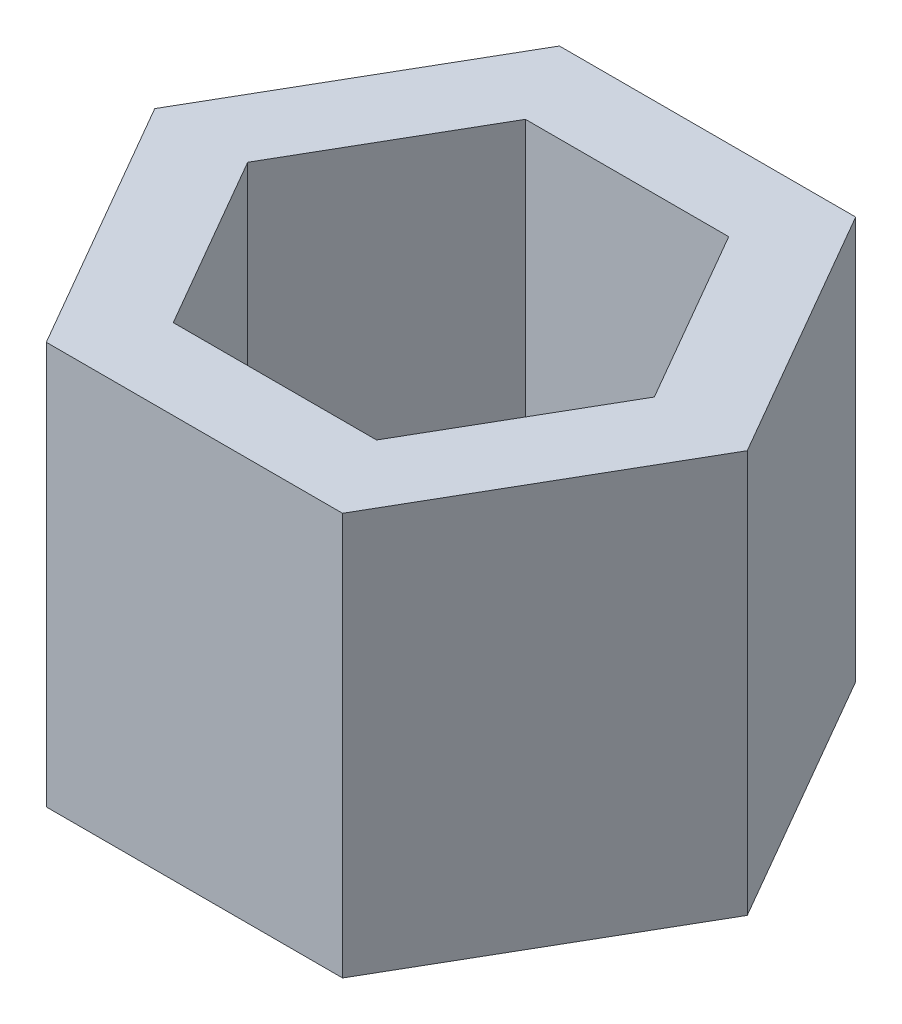
SolidWorks part; units mm, degrees
ref_plane "Front Plane" through (0, 0, 0) normal (0, 0, 1) x (1, 0, 0)
ref_plane "Top Plane" through (0, 0, 0) normal (0, 1, 0) x (1, 0, 0)
ref_plane "Right Plane" through (0, 0, 0) normal (1, 0, 0) x (0, 0, -1)
sketch "Sketch1" plane through (0, 0, 0) normal (0, 1, 0) x (1, 0, 0)
  line L0 (2.5259, 4.375) -> (-2.5259, 4.375)
  line L1 (7.3612, 0) -> (3.6806, 6.375)
  line L2 (3.6806, 6.375) -> (-3.6806, 6.375)
  line L3 (-3.6806, 6.375) -> (-7.3612, 0)
  line L4 (-7.3612, 0) -> (-3.6806, -6.375)
  line L5 (-3.6806, -6.375) -> (3.6806, -6.375)
  line L6 (3.6806, -6.375) -> (7.3612, 0)
  line L7 (-2.5259, 4.375) -> (-5.0518, 0)
  line L8 (-5.0518, 0) -> (-2.5259, -4.375)
  line L9 (-2.5259, -4.375) -> (2.5259, -4.375)
  line L10 (2.5259, -4.375) -> (5.0518, 0)
  line L11 (5.0518, 0) -> (2.5259, 4.375)
  circle A0 centre (0, 0) radius 6.375 construction
  dimension "D2" = 12.75
  dimension "D1" = 2
extrude "Boss-Extrude1" add sketch "Sketch1" along normal blind 10
